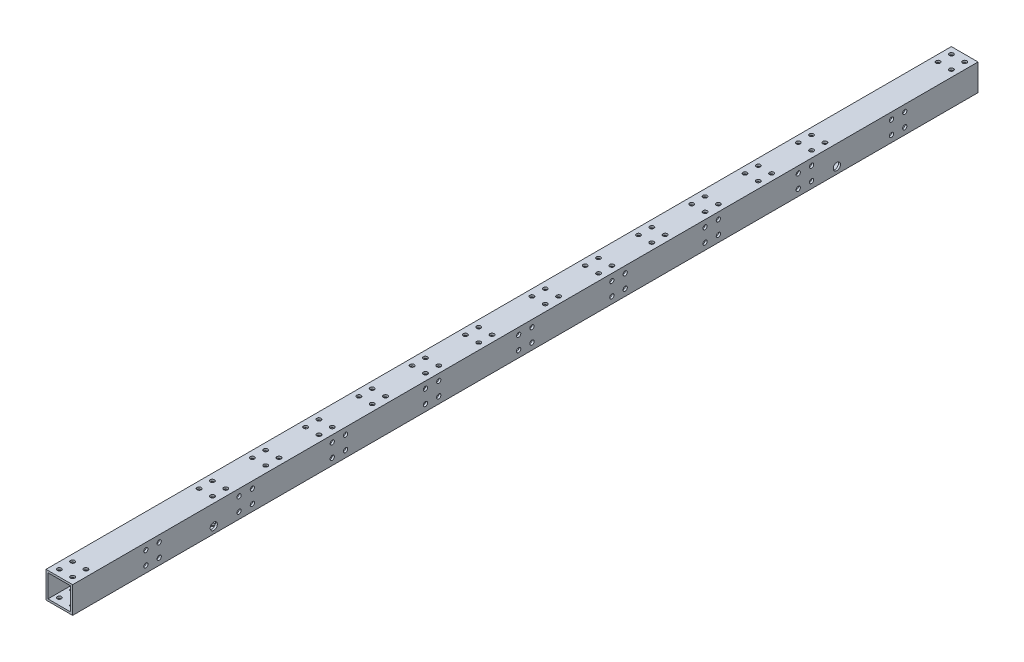
SolidWorks part; units mm, degrees
ref_plane "前视基准面" through (0, 0, 0) normal (0, 0, 1) x (1, 0, 0)
ref_plane "上视基准面" through (0, 0, 0) normal (0, 1, 0) x (1, 0, 0)
ref_plane "右视基准面" through (0, 0, 0) normal (1, 0, 0) x (0, 0, -1)
other "Configuration Table"
sketch "草图1" plane through (0, 0, 0) normal (0, 0, 1) x (1, 0, 0)
  line L1 (0, 0) -> (20, 0)
  line L2 (0, 0) -> (0, -20)
  line L3 (0, -20) -> (20, -20)
  line L4 (20, 0) -> (20, -20)
  dimension "D1" = 20
  dimension "D2" = 20
extrude "拉伸-薄壁1" add sketch "草图1" along normal blind 680 thin
sketch "草图2" plane through (0, 0, 0) normal (0, 1, 0) x (1, 0, 0)
  line L0 (10, 0) -> (10, -195) construction
  line L1 (20, 0) -> (0, 0) construction
  line L2 (0, -340) -> (20, -340) construction
  line L3 (0, -680) -> (0, 0) construction
  line L4 (20, -680) -> (20, 0) construction
  line L5 (0, -10) -> (20, -10) construction
  line L6 (0, -445) -> (20, -445) construction
  line L7 (0, -235) -> (20, -235) construction
  line L8 (20, -680) -> (0, -680) construction
  line L9 (20, -465) -> (0, -465) construction
  line L10 (0, -485) -> (20, -485) construction
  line L11 (20, -215) -> (0, -215) construction
  line L12 (0, -195) -> (20, -195) construction
  circle A0 centre (5, -5) radius 1.575
  circle A1 centre (15, -5) radius 1.575
  circle A2 centre (15, -675) radius 1.575
  circle A3 centre (5, -675) radius 1.575
  circle A4 centre (15, -15) radius 1.575
  circle A5 centre (5, -15) radius 1.575
  circle A6 centre (5, -665) radius 1.575
  circle A7 centre (15, -665) radius 1.575
  circle A8 centre (5, -450) radius 1.575
  circle A9 centre (15, -450) radius 1.575
  circle A10 centre (15, -440) radius 1.575
  circle A11 centre (5, -440) radius 1.575
  circle A12 centre (5, -240) radius 1.575
  circle A13 centre (15, -240) radius 1.575
  circle A14 centre (15, -230) radius 1.575
  circle A15 centre (5, -230) radius 1.575
  circle A16 centre (5, -490) radius 1.575
  circle A17 centre (15, -490) radius 1.575
  circle A18 centre (15, -480) radius 1.575
  circle A19 centre (5, -480) radius 1.575
  circle A20 centre (5, -200) radius 1.575
  circle A21 centre (15, -200) radius 1.575
  circle A22 centre (15, -190) radius 1.575
  circle A23 centre (5, -190) radius 1.575
  circle A24 centre (5, -270) radius 1.575
  circle A25 centre (15, -270) radius 1.575
  circle A26 centre (5, -280) radius 1.575
  circle A27 centre (15, -280) radius 1.575
  circle A28 centre (5, -310) radius 1.575
  circle A29 centre (5, -320) radius 1.575
  circle A30 centre (15, -310) radius 1.575
  circle A31 centre (15, -320) radius 1.575
  circle A32 centre (15, -360) radius 1.575
  circle A33 centre (15, -370) radius 1.575
  circle A34 centre (5, -360) radius 1.575
  circle A35 centre (5, -370) radius 1.575
  circle A36 centre (15, -400) radius 1.575
  circle A37 centre (5, -400) radius 1.575
  circle A38 centre (15, -410) radius 1.575
  circle A39 centre (5, -410) radius 1.575
  circle A40 centre (15, -110) radius 1.575
  circle A41 centre (15, -120) radius 1.575
  circle A42 centre (5, -110) radius 1.575
  circle A43 centre (5, -120) radius 1.575
  circle A44 centre (15, -150) radius 1.575
  circle A45 centre (5, -150) radius 1.575
  circle A46 centre (15, -160) radius 1.575
  circle A47 centre (5, -160) radius 1.575
  circle A48 centre (5, -520) radius 1.575
  circle A49 centre (15, -520) radius 1.575
  circle A50 centre (5, -530) radius 1.575
  circle A51 centre (15, -530) radius 1.575
  circle A52 centre (5, -560) radius 1.575
  circle A53 centre (5, -570) radius 1.575
  circle A54 centre (15, -560) radius 1.575
  circle A55 centre (15, -570) radius 1.575
  point P106 (10, -166.6073)
  point P107 (10, -195)
  dimension "D1" = 3.15
  dimension "D6" = 3.15
  dimension "D2" = 5
  dimension "D3" = 5
  dimension "D4" = 10
  dimension "D5" = 235
  dimension "D7" = 5
  dimension "D8" = 5
  dimension "D9" = 215
  dimension "D10" = 70
extrude "切除-拉伸1" cut sketch "草图2" against normal through all
sketch "草图3" plane through (0, 0, 0) normal (-1, 0, 0) x (0, 0, 1)
  line L0 (680, -20) -> (0, -20) construction
  line L1 (0, 0) -> (0, -20) construction
  line L2 (340, -20) -> (340, 0) construction
  line L3 (680, 0) -> (0, 0) construction
  line L4 (340, -10) -> (0, -10) construction
  circle A0 centre (106, -15) radius 2.7
  circle A1 centre (574, -15) radius 2.7
  circle A2 centre (335, -5) radius 1.6
  circle A3 centre (335, -15) radius 1.6
  circle A4 centre (345, -15) radius 1.6
  circle A5 centre (345, -5) radius 1.6
  circle A6 centre (265, -5) radius 1.6
  circle A7 centre (275, -5) radius 1.6
  circle A8 centre (265, -15) radius 1.6
  circle A9 centre (275, -15) radius 1.6
  circle A10 centre (195, -5) radius 1.6
  circle A11 centre (205, -5) radius 1.6
  circle A12 centre (195, -15) radius 1.6
  circle A13 centre (205, -15) radius 1.6
  circle A14 centre (125, -5) radius 1.6
  circle A15 centre (135, -5) radius 1.6
  circle A16 centre (125, -15) radius 1.6
  circle A17 centre (135, -15) radius 1.6
  circle A18 centre (55, -5) radius 1.6
  circle A19 centre (65, -5) radius 1.6
  circle A20 centre (55, -15) radius 1.6
  circle A21 centre (65, -15) radius 1.6
  circle A22 centre (615, -15) radius 1.6
  circle A23 centre (625, -15) radius 1.6
  circle A24 centre (615, -5) radius 1.6
  circle A25 centre (625, -5) radius 1.6
  circle A26 centre (545, -15) radius 1.6
  circle A27 centre (555, -15) radius 1.6
  circle A28 centre (545, -5) radius 1.6
  circle A29 centre (555, -5) radius 1.6
  circle A30 centre (475, -15) radius 1.6
  circle A31 centre (485, -15) radius 1.6
  circle A32 centre (475, -5) radius 1.6
  circle A33 centre (485, -5) radius 1.6
  circle A34 centre (405, -15) radius 1.6
  circle A35 centre (415, -15) radius 1.6
  circle A36 centre (405, -5) radius 1.6
  circle A37 centre (415, -5) radius 1.6
  dimension "D1" = 5.4
  dimension "D4" = 3.2
  dimension "D2" = 5
  dimension "D3" = 106
  dimension "D5" = 5
  dimension "D6" = 5
  dimension "D7" = 60
extrude "切除-拉伸2" cut sketch "草图3" against normal through all
